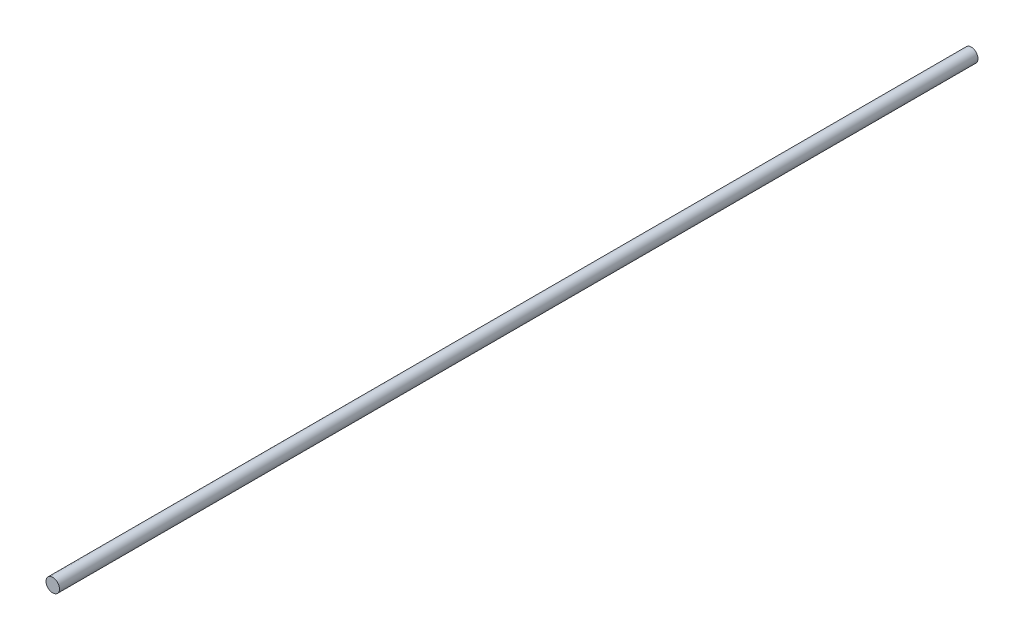
SolidWorks part; units mm, degrees
ref_plane "Front Plane" through (0, 0, 0) normal (0, 0, 1) x (1, 0, 0)
ref_plane "Top Plane" through (0, 0, 0) normal (0, 1, 0) x (1, 0, 0)
ref_plane "Right Plane" through (0, 0, 0) normal (1, 0, 0) x (0, 0, -1)
sketch "Sketch1" plane through (0, 0, 0) normal (0, 0, 1) x (1, 0, 0)
  circle A0 centre (0, 0) radius 4
  dimension "D1" = 8
extrude "Boss-Extrude1" add sketch "Sketch1" along normal blind 544
